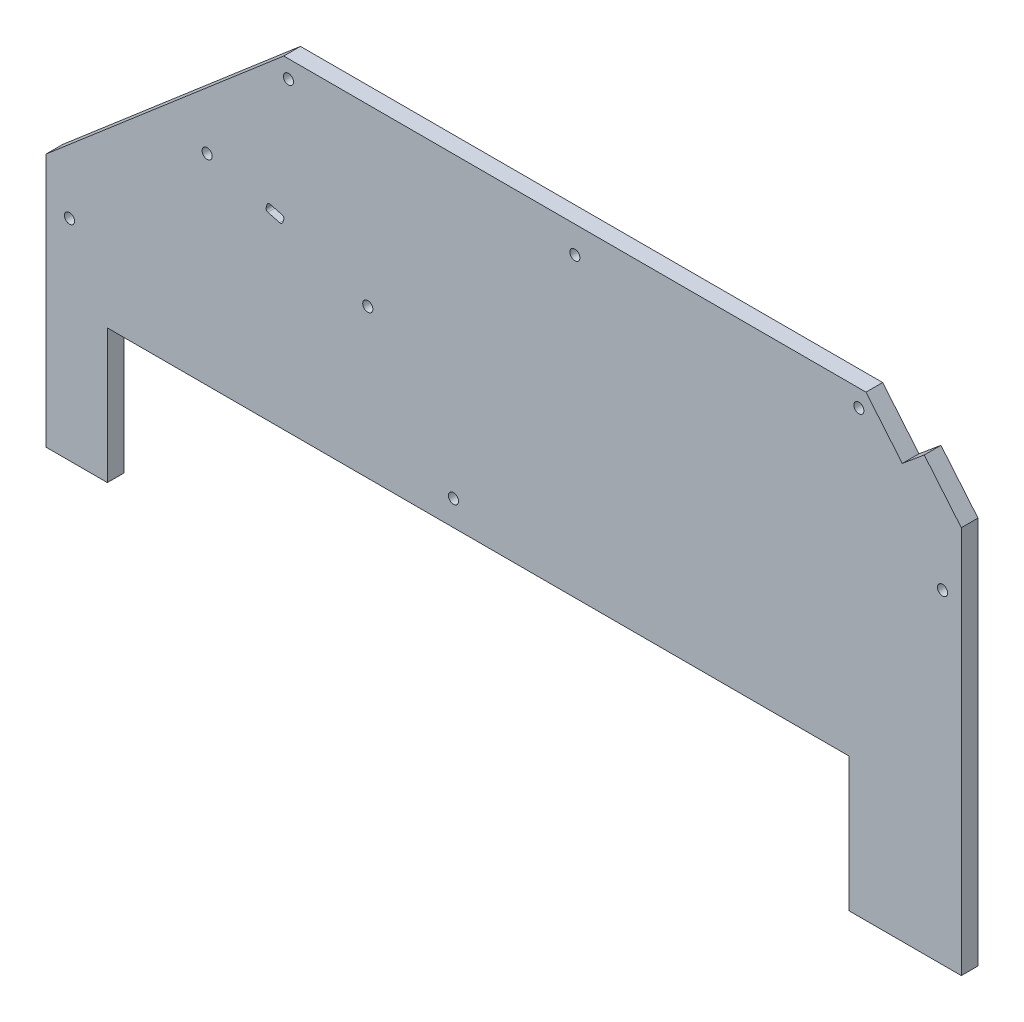
SolidWorks part; units mm, degrees
ref_plane "Front Plane" through (0, 0, 0) normal (0, 0, 1) x (1, 0, 0)
ref_plane "Top Plane" through (0, 0, 0) normal (0, 1, 0) x (1, 0, 0)
ref_plane "Right Plane" through (0, 0, 0) normal (1, 0, 0) x (0, 0, -1)
sketch "Sketch1" plane through (0, 0, 0) normal (0, 0, 1) x (1, 0, 0)
  line L1 (-629.05, -12.5) -> (-568.725, -12.5)
  line L2 (-629.05, -12.5) -> (-629.05, 139.9)
  line L4 (-568.725, -12.5) -> (-568.725, 76.762)
  line L6 (0, -12.5) -> (0, 216.1)
  line L9 (-451.25, 292.3) -> (-629.05, 139.9)
  line L10 (0, 216.1) -> (-63.5, 292.3)
  line L11 (-63.5, 292.3) -> (-451.25, 292.3)
  line L12 (0, 1140.6125) -> (0, 23.6125) construction
  line L13 (-451.25, 292.3) -> (-451.25, 188.3086) construction
  line L14 (-465.855, 76) -> (-550.945, 76) construction
  line L15 (-460.4286, 202.2879) -> (-452.3363, 200.1995)
  line L17 (-74.8137, 23.6125) -> (-74.8137, 12.5) construction
  line L21 (-74.8137, -12.5) -> (-74.8137, 76.762)
  line L23 (-451.2256, 198.1646) -> (-451.9931, 195.8403)
  line L24 (0, -12.5) -> (-74.8137, -12.5)
  line L26 (-15, 203.6) -> (-10, 203.6) construction
  line L27 (-15, 1140.6125) -> (-15, 23.6125) construction
  line L28 (-10, 23.6125) -> (-10, 1140.6125) construction
  line L29 (2.9156, 206.9655) -> (2.9156, 200.2345) construction
  line L30 (19.05, 206.9655) -> (0, 206.9655) construction
  line L31 (0, 200.2345) -> (19.05, 200.2345) construction
  line L32 (2.9156, 200.2345) -> (2.9156, 203.6) construction
  line L33 (2.9156, 203.6) -> (-12.5, 203.6) construction
  line L34 (-453.8973, 194.801) -> (-461.8322, 196.8487)
  line L35 (-568.725, 76.762) -> (-74.8137, 76.762)
  line L36 (-568.725, 23.6125) -> (-568.725, 12.5) construction
  line L37 (-462.9727, 198.7825) -> (-462.3624, 201.1474)
  circle A0 centre (-12.5, 203.6) radius 3.3782
  arc A3 (-462.9727, 198.7825) -> (-461.8322, 196.8487) centre (-461.4355, 198.3859) ccw
  arc A4 (-453.8973, 194.801) -> (-451.9931, 195.8403) centre (-453.5006, 196.3381) ccw
  arc A5 (-451.2256, 198.1646) -> (-452.3363, 200.1995) centre (-452.733, 198.6624) ccw
  arc A6 (-462.3624, 201.1474) -> (-460.4286, 202.2879) centre (-460.8253, 200.7507) cw
  dimension "D12" = 6.7564
  dimension "D5" = 1.5875
  dimension "D1" = 90
  dimension "D2" = 228.6
  dimension "D3" = 304.8
  dimension "D4" = 0.762
  dimension "D7" = 177.8
  dimension "D8" = 63.5
extrude "Boss-Extrude1" add sketch "Sketch1" along normal blind 11.1125
extrude "Cut-Extrude1" cut sketch "Sketch2" against normal through all
sketch "Sketch2" plane through (-305, 23.6125, -5.08) normal (0, 0, -1) x (-1, 0, 0)
  line L3 (286.0006, 108.8288) -> (291.9061, 98.6002) construction
  circle A0 centre (288.9534, 103.7145) radius 3.3655
extrude "Cut-Extrude2" cut sketch "Sketch3" against normal through all
sketch "Sketch3" plane through (-305, 23.6125, -1.905) normal (0, 0, -1) x (-1, 0, 0)
  line L0 (144.3708, 263.6075) -> (141.8617, 250.2021) construction
  circle A0 centre (143.1163, 256.9048) radius 3.3655
extrude "Cut-Extrude3" cut sketch "Sketch4" against normal through all
sketch "Sketch4" plane through (-305, 23.6125, -1.905) normal (0, 0, -1) x (-1, 0, 0)
  line L1 (-47.625, 256.813) -> (-47.625, 245.002) construction
  circle A0 centre (-47.625, 250.9075) radius 3.3655
extrude "Cut-Extrude4" cut sketch "Sketch5" against normal through all
sketch "Sketch5" plane through (-305, 23.6125, -1.905) normal (0, 0, -1) x (-1, 0, 0)
  line L1 (-231.2242, 259.2462) -> (-242.3091, 255.169) construction
  circle A0 centre (-236.7667, 257.2076) radius 3.3655
extrude "Cut-Extrude5" cut sketch "Sketch6" against normal through all both and the other way through all
sketch "Sketch6" plane through (-305, 23.6125, 18.7325) normal (0, 0, 1) x (1, 0, 0)
  circle A0 centre (-197.2621, 186.927) radius 3.3782
  circle A2 centre (-33.2097, 70.0054) radius 3.3782
  circle A3 centre (-90.297, 152.235) radius 3.3782
sketch "Sketch7" plane through (0, 0, 11.1125) normal (0, 0, 1) x (1, 0, 0)
  line L0 (0, -12.5) -> (-609.6, -12.5) construction
  line L2 (-629.05, 139.9) -> (-629.05, -12.5) construction
  line L3 (-609.6, -12.5) -> (-629.05, -12.5)
  line L4 (-609.6, -12.5) -> (-609.6, 156.5714)
  line L5 (-609.6, 156.5714) -> (-629.05, 156.5714)
  line L6 (-629.05, -12.5) -> (-629.05, 156.5714)
  line L7 (-451.25, 292.3) -> (-629.05, 139.9) construction
  dimension "D1" = 609.6
extrude "Cut-Extrude6" cut sketch "Sketch7" against normal through all contours L4 L3 L6 L5
sketch "Sketch9" plane through (0, 0, 11.1125) normal (0, 0, 1) x (1, 0, 0)
  line L0 (0, 216.1) -> (0, 245.8571)
  line L1 (0, 245.8571) -> (-24.6799, 275.4729)
  line L2 (-24.6799, 275.4729) -> (-39.3145, 263.2774)
  line L3 (0, 216.1) -> (-63.5, 292.3) construction
  line L4 (-39.3145, 263.2774) -> (0, 216.1)
  line L5 (-25, 275.8571) -> (-39.6346, 263.6615) construction
  line L7 (-48.8654, 304.4955) -> (6.3334, 238.2569) construction
  dimension "D1" = 0.5
extrude "Boss-Extrude2" add sketch "Sketch9" against normal up to vertex (11.1125 mm away) up to point (0, 216.1, 0)
